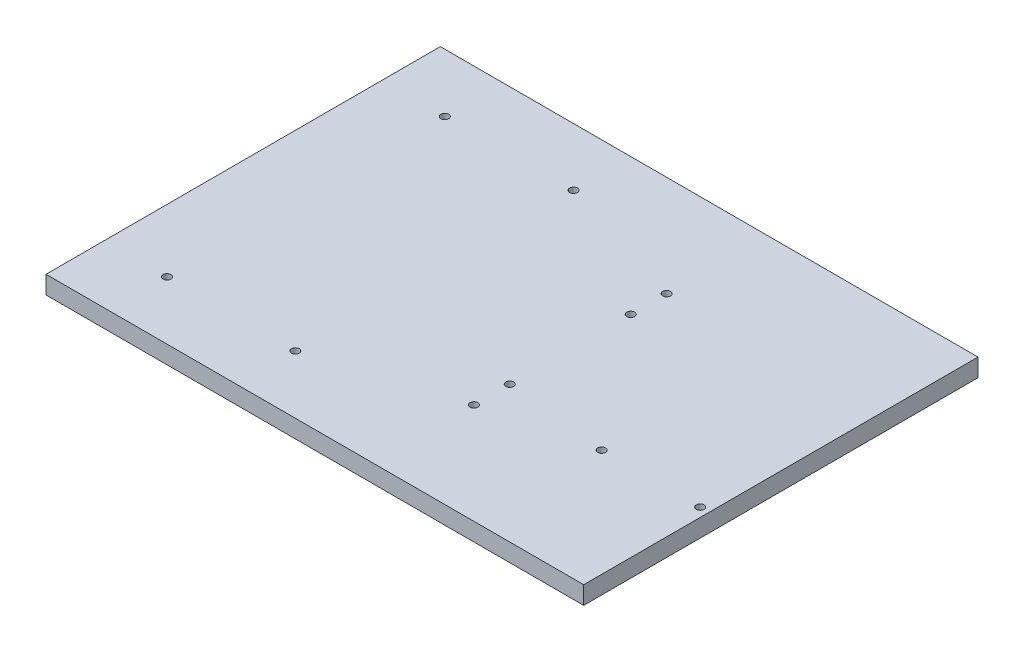
SolidWorks part; units mm, degrees
material "Beech"
ref_plane "Front Plane" through (0, 0, 0) normal (0, 0, 1) x (1, 0, 0)
ref_plane "Top Plane" through (0, 0, 0) normal (0, 1, 0) x (1, 0, 0)
ref_plane "Right Plane" through (0, 0, 0) normal (1, 0, 0) x (0, 0, -1)
sketch "Sketch1" plane through (0, 0, 0) normal (0, 1, 0) x (1, 0, 0)
  line L1 (0, 0) -> (304.8, 0)
  line L2 (0, 0) -> (0, 304.8)
  line L3 (0, 304.8) -> (304.8, 304.8)
  line L4 (304.8, 0) -> (304.8, 304.8)
  dimension "D1" = 304.8
  dimension "D2" = 304.8
extrude "Boss-Extrude1" add sketch "Sketch1" along normal blind 6.35
sketch "Sketch2" plane through (0, 6.35, 0) normal (0, 1, 0) x (1, 0, 0)
  line L1 (304.8, 304.8) -> (0, 304.8) construction
  line L2 (190.5, 304.8) -> (190.5, 165.1)
  line L3 (190.5, 165.1) -> (0, 165.1)
  line L4 (0, 304.8) -> (0, 0) construction
  line L6 (0, 165.1) -> (0, 0)
  line L7 (0, 0) -> (304.8, 0)
  line L8 (304.8, 0) -> (304.8, 304.8)
  line L9 (304.8, 304.8) -> (190.5, 304.8)
extrude "Cut-Extrude1" cut sketch "Sketch2" against normal through all
sketch "Sketch3" plane through (0, 6.35, 0) normal (0, 1, 0) x (1, 0, 0)
  line L0 (0, 304.8) -> (0, 165.1) construction
  line L1 (190.5, 165.1) -> (0, 165.1) construction
  line L2 (190.5, 304.8) -> (0, 304.8) construction
  circle A0 centre (22.225, 185.7375) radius 1.3891
  circle A1 centre (67.691, 185.7375) radius 1.3891
  circle A2 centre (22.225, 284.1625) radius 1.3891
  circle A3 centre (67.691, 284.3204) radius 1.3891
  dimension "D1" = 2.7781
  dimension "D3" = 2.7781
  dimension "D5" = 20.6375
  dimension "D6" = 2.7781
  dimension "D7" = 2.7781
  dimension "D8" = 20.6375
  dimension "D2" = 22.225
  dimension "D4" = 45.466
extrude "Cut-Extrude2" cut sketch "Sketch3" against normal through all
sketch "Sketch4" plane through (0, 6.35, 0) normal (0, 1, 0) x (1, 0, 0)
  line L0 (190.5, 304.8) -> (0, 304.8) construction
  line L1 (190.5, 304.8) -> (190.5, 165.1) construction
  line L2 (190.5, 165.1) -> (0, 165.1) construction
  circle A0 centre (115.8875, 269.0813) radius 1.3891
  circle A1 centre (115.8875, 256.3813) radius 1.3891
  circle A2 centre (115.8875, 200.8188) radius 1.3891
  circle A3 centre (115.8875, 213.5188) radius 1.3891
  dimension "D1" = 35.7188
  dimension "D2" = 2.7781
  dimension "D4" = 48.4187
  dimension "D5" = 2.7781
  dimension "D6" = 2.7781
  dimension "D7" = 2.7781
  dimension "D8" = 74.6125
  dimension "D9" = 48.4187
  dimension "D11" = 0
  dimension "D3" = 74.6125
  dimension "D10" = 0
extrude "Cut-Extrude3" cut sketch "Sketch4" against normal through all
sketch "Sketch5" plane through (0, 6.35, 0) normal (0, 1, 0) x (1, 0, 0)
  line L0 (190.5, 304.8) -> (190.5, 165.1) construction
  line L1 (190.5, 165.1) -> (0, 165.1) construction
  circle A0 centre (187.325, 209.55) radius 1.3891
  circle A1 centre (152.4, 209.55) radius 1.3891
  dimension "D1" = 3.175
  dimension "D2" = 2.7781
  dimension "D3" = 44.45
  dimension "D5" = 2.7781
  dimension "D4" = 34.925
extrude "Cut-Extrude4" cut sketch "Sketch5" against normal through all
